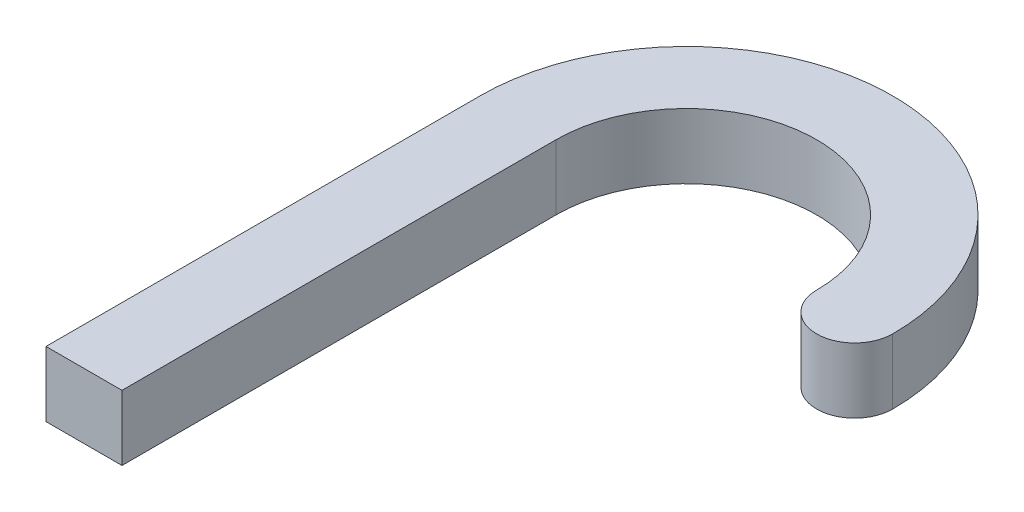
SolidWorks part; units mm, degrees
ref_plane "Front Plane" through (0, 0, 0) normal (0, 0, 1) x (1, 0, 0)
ref_plane "Top Plane" through (0, 0, 0) normal (0, 1, 0) x (1, 0, 0)
ref_plane "Right Plane" through (0, 0, 0) normal (1, 0, 0) x (0, 0, -1)
sketch "Sketch1" plane through (0, 0, 0) normal (0, 1, 0) x (1, 0, 0)
  line L5 (0, 0) -> (3.5, 0)
  line L6 (0, 0) -> (0, 20)
  line L8 (3.5, 0) -> (3.5, 20)
  arc A0 (0, 20) -> (19, 20) centre (9.5, 20) cw
  arc A1 (19, 20) -> (15.5, 20) centre (17.25, 20) cw
  arc A2 (15.5, 20) -> (3.5, 20) centre (9.5, 20) ccw
  point P4 (0, 0)
  point P11 (7.0833, 10.7362)
  point P12 (0, 0)
  point P13 (12.9456, 10.2324)
  point P14 (9.1051, 17.5983)
  point P15 (15.5051, 17.6137)
  point P16 (14.4797, 16.0068)
  point P17 (16.9063, 15.9623)
  point P18 (10.4382, 20)
  point P19 (10.1416, 20.192)
  point P20 (25.1149, 18.5532)
  point P21 (0, 0)
  point P22 (25.6043, 19.7413)
  point P23 (26.0409, 20)
  dimension "D2" = 1.75
  dimension "D3" = 12
  dimension "D1" = 20
  dimension "D4" = 3.5
extrude "Boss-Extrude1" add sketch "Sketch1" along normal blind 3
